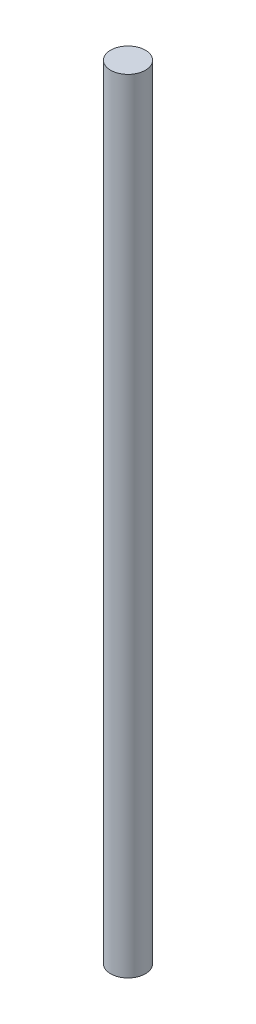
SolidWorks part; units mm, degrees
ref_plane "前视基准面" through (0, 0, 0) normal (0, 0, 1) x (1, 0, 0)
ref_plane "上视基准面" through (0, 0, 0) normal (0, 1, 0) x (1, 0, 0)
ref_plane "右视基准面" through (0, 0, 0) normal (1, 0, 0) x (0, 0, -1)
other "Configuration Table"
sketch "草图1" plane through (0, 0, 0) normal (0, 1, 0) x (1, 0, 0)
  circle A0 centre (0, 0) radius 1
  dimension "D1" = 2
extrude "凸台-拉伸1" add sketch "草图1" along normal blind 45
